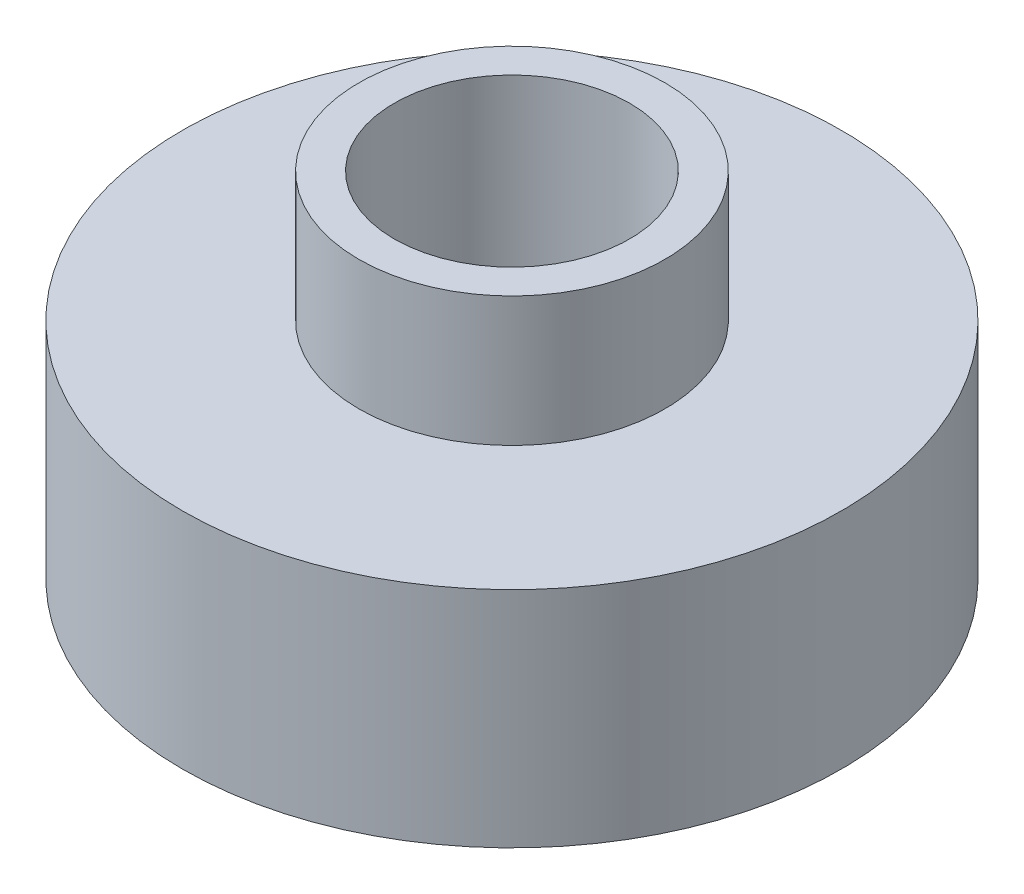
SolidWorks part; units mm, degrees
ref_plane "Front Plane" through (0, 0, 0) normal (0, 0, 1) x (1, 0, 0)
ref_plane "Top Plane" through (0, 0, 0) normal (0, 1, 0) x (1, 0, 0)
ref_plane "Right Plane" through (0, 0, 0) normal (1, 0, 0) x (0, 0, -1)
sketch "Sketch1" plane through (0, 0, 0) normal (0, 0, 1) x (1, 0, 0)
  line L0 (0, 93.4932) -> (0, -90.8962) construction
  line L1 (56, 0) -> (48, 0)
  line L2 (48, 0) -> (48, 28)
  line L3 (48, 28) -> (20, 28)
  line L4 (20, 28) -> (20, 60)
  line L5 (26, 60) -> (20, 60)
  line L6 (56, 38) -> (26, 38)
  line L7 (56, 38) -> (56, 0)
  line L8 (26, 38) -> (26, 60)
  point P9 (54, -5.6767)
  point P10 (54, 34)
  dimension "D2" = 40
  dimension "D1" = 38
  dimension "D3" = 96
  dimension "D4" = 112
  dimension "D5" = 28
  dimension "D6" = 60
  dimension "D7" = 52
revolve "Revolve1" add sketch "Sketch1" angle 360 about L0
